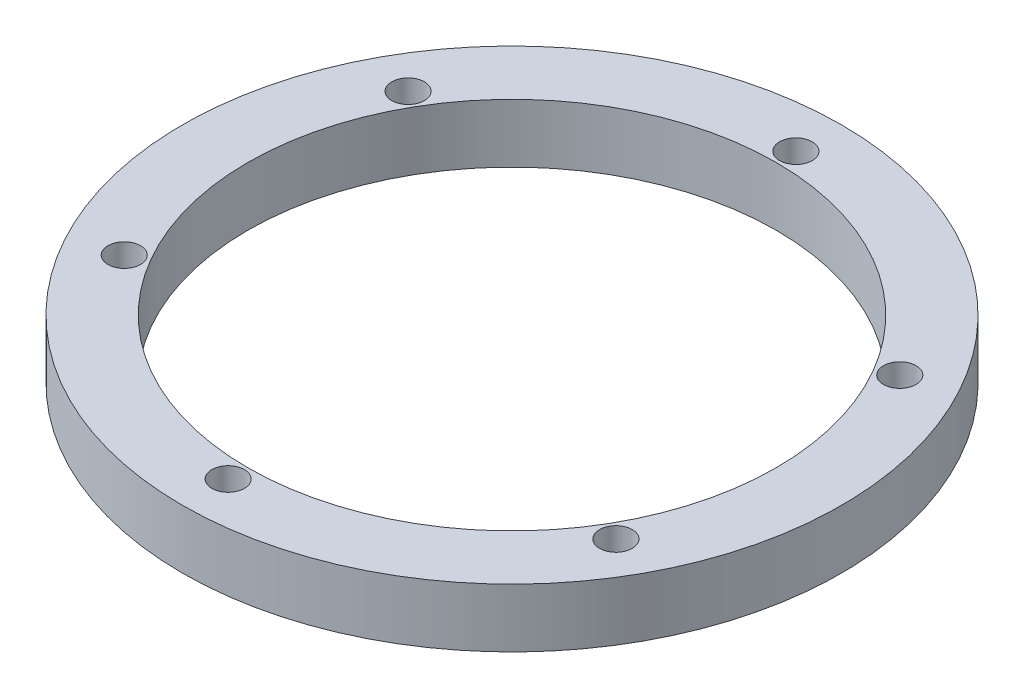
SolidWorks part; units mm, degrees
material "ABS"
ref_plane "Front Plane" through (0, 0, 0) normal (0, 0, 1) x (1, 0, 0)
ref_plane "Top Plane" through (0, 0, 0) normal (0, 1, 0) x (1, 0, 0)
ref_plane "Right Plane" through (0, 0, 0) normal (1, 0, 0) x (0, 0, -1)
sketch "Sketch1" plane through (0, 0, 0) normal (0, 1, 0) x (1, 0, 0)
  circle A0 centre (0, 0) radius 40.5
  circle A1 centre (0, 0) radius 50.5
  dimension "D2" = 81
  dimension "D1" = 10
extrude "Boss-Extrude1" add sketch "Sketch1" along normal blind 9
sketch "Sketch2" plane through (0, 9, 0) normal (0, 1, 0) x (1, 0, 0)
  circle A0 centre (0, 0) radius 43.5 construction
  circle A1 centre (0, 43.5) radius 2.5
  circle A2 centre (37.6721, 21.75) radius 2.5
  circle A3 centre (37.6721, -21.75) radius 2.5
  circle A4 centre (0, -43.5) radius 2.5
  circle A5 centre (-37.6721, -21.75) radius 2.5
  circle A6 centre (-37.6721, 21.75) radius 2.5
  dimension "D1" = 87
  dimension "D2" = 5
  dimension "D3" = 6
extrude "Cut-Extrude1" cut sketch "Sketch2" against normal blind 9
